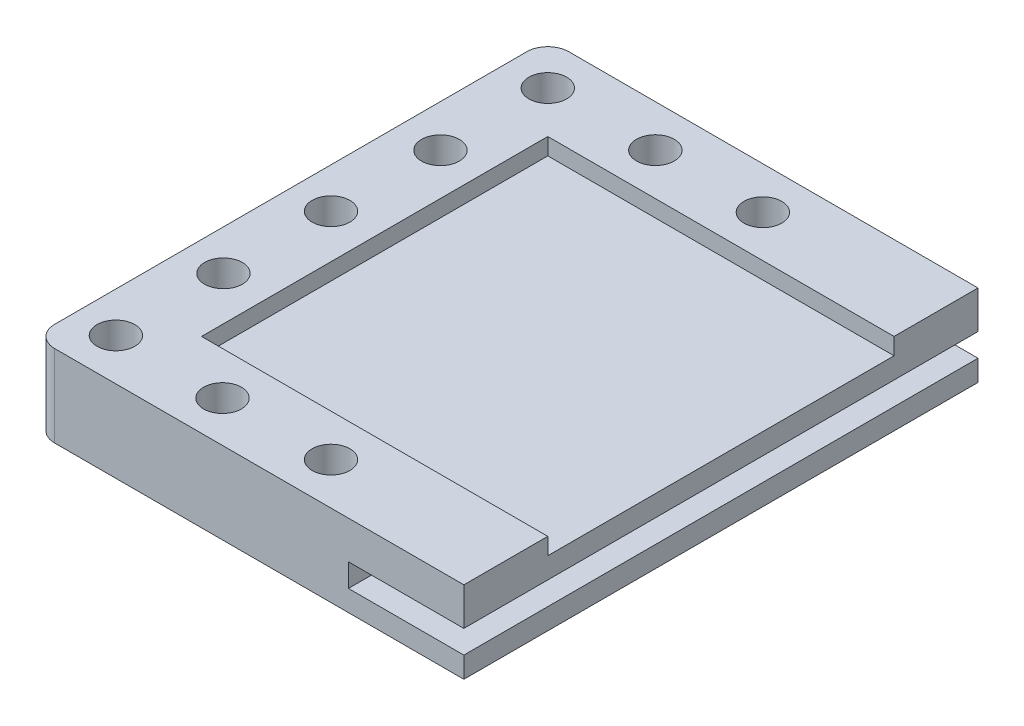
SolidWorks part; units mm, degrees
ref_plane "Front Plane" through (0, 0, 0) normal (0, 0, 1) x (1, 0, 0)
ref_plane "Top Plane" through (0, 0, 0) normal (0, 1, 0) x (1, 0, 0)
ref_plane "Right Plane" through (0, 0, 0) normal (1, 0, 0) x (0, 0, -1)
sketch "Sketch1" plane through (0, 0, 0) normal (0, 1, 0) x (1, 0, 0)
  line L1 (-14.684, 10.0891) -> (5.816, 10.0891)
  line L2 (-14.684, 10.0891) -> (-14.684, -14.4109)
  line L3 (-14.684, -14.4109) -> (5.816, -14.4109)
  line L4 (5.816, 10.0891) -> (5.816, -14.4109)
  dimension "D1" = 20.5
  dimension "D2" = 24.5
extrude "Boss-Extrude1" add sketch "Sketch1" along normal blind 3.1
sketch "Sketch2" plane through (0, 0, 14.4109) normal (0, 0, 1) x (1, 0, 0)
  line L0 (5.816, 3.1) -> (5.816, 0) construction
  line L1 (5.816, 2.1) -> (0.316, 2.1)
  line L2 (5.816, 2.1) -> (5.816, 1)
  line L3 (5.816, 1) -> (0.316, 1)
  line L4 (0.316, 2.1) -> (0.316, 1)
  line L5 (-14.684, 3.1) -> (5.816, 3.1) construction
  dimension "D1" = 5.5
  dimension "D2" = 1.1
  dimension "D3" = 1
extrude "Cut-Extrude1" cut sketch "Sketch2" against normal through all
sketch "Sketch3" plane through (0, 3.1, 0) normal (0, 1, 0) x (1, 0, 0)
  line L0 (-14.684, -14.4109) -> (5.816, -14.4109) construction
  line L1 (-14.684, 10.0891) -> (-10.684, 10.0891)
  line L2 (-14.684, 10.0891) -> (-14.684, -14.4109)
  line L3 (-14.684, -14.4109) -> (-10.684, -14.4109)
  line L4 (-10.684, 10.0891) -> (-10.684, -14.4109)
  line L5 (5.816, -14.4109) -> (5.816, 10.0891) construction
  line L6 (-10.684, 10.0891) -> (5.816, 10.0891)
  line L7 (-10.684, 10.0891) -> (-10.684, 6.0891)
  line L8 (-10.684, 6.0891) -> (5.816, 6.0891)
  line L9 (5.816, 10.0891) -> (5.816, 6.0891)
  line L11 (-10.684, -14.4109) -> (5.816, -14.4109)
  line L12 (-10.684, -14.4109) -> (-10.684, -10.4109)
  line L13 (-10.684, -10.4109) -> (5.816, -10.4109)
  line L14 (5.816, -14.4109) -> (5.816, -10.4109)
  line M7 (-14.684, 10.0891) -> (-14.684, -14.4109)
  line M8 (-14.684, -14.4109) -> (5.816, -14.4109)
  line M9 (5.816, -14.4109) -> (5.816, 10.0891)
  line M10 (5.816, 10.0891) -> (-14.684, 10.0891)
  dimension "D1" = 4
  dimension "D2" = 4
  dimension "D3" = 4
extrude "Boss-Extrude2" add sketch "Sketch3" along normal blind 0.8 contours L4 M10 M7 M8 | L4 L8 M9 M10 | L13 L4 M8 M9
sketch "Sketch4" plane through (0, 0, 0) normal (0, -1, 0) x (1, 0, 0)
  line L0 (5.816, 14.4109) -> (5.816, -10.0891) construction
  line L1 (5.816, -10.0891) -> (-14.684, -10.0891) construction
  circle A0 centre (3.066, -5.3391) radius 0.5501
  circle A5 centre (3.066, 4.6609) radius 0.5501
  circle A6 centre (3.066, -0.3391) radius 0.5501
  circle A7 centre (3.0468, 9.6608) radius 0.5501
  dimension "D1" = 2.75
  dimension "D2" = 5
  dimension "D3" = 5
  dimension "D4" = 5
  dimension "D5" = 4.75
  dimension "D6" = 0
  dimension "D7" = 0
hole_wizard "Tap Drill for M2.5x0.45 Tap1" positions "Sketch5" profile "Sketch6" hole size "M2.5x0.45" standard "ANSI Metric"
sketch "Sketch5" plane through (0, 0, 0) normal (0, -1, 0) x (-1, 0, 0)
  point P0 (-3.066, 5.3391)
  point P3 (-3.066, 0.3391)
  point P6 (-3.066, -4.6609)
  point P9 (-3.0468, -9.6608)
sketch "Sketch6" plane through (3.066, 0, -5.3391) normal (1, 0, 0) x (0, 0, -1)
  line L0 (0, 0) -> (0, 1.675)
  line L1 (0, 1.675) -> (1.125, 0.999)
  line L2 (1.125, 0.999) -> (1.125, 0)
  line L5 (1.125, 0) -> (0, 0)
  line L10 (0, 1.675) -> (-1.125, 0.999) construction
  line L11 (0, -6.35) -> (0, 107.95) construction
  dimension "Hole Dia." = 2.25
  dimension "Hole Depth" = 0.999
  dimension "Drill Angle" = 118
sketch "Sketch7" plane through (0, 3.9, 0) normal (0, 1, 0) x (1, 0, 0)
  line L0 (-14.684, 10.0891) -> (-14.684, -14.4109) construction
  line L2 (5.816, 10.0891) -> (-14.684, 10.0891) construction
  circle A0 centre (-12.684, 8.0891) radius 0.882
  circle A1 centre (-12.7647, -12.4109) radius 0.882
  circle A2 centre (-12.6745, 2.9641) radius 0.882
  circle A3 centre (-12.7647, -2.1609) radius 0.882
  circle A4 centre (-12.7647, -7.2859) radius 0.882
  circle A5 centre (-7.559, 8.0891) radius 0.882
  circle A6 centre (-2.434, 8.0891) radius 0.882
  circle A7 centre (-2.5147, -12.4109) radius 0.882
  circle A9 centre (-7.6397, -12.4567) radius 0.882
  dimension "D1" = 2
  dimension "D2" = 2
  dimension "D3" = 5.125
  dimension "D4" = 5.125
  dimension "D5" = 5.125
  dimension "D6" = 5.125
  dimension "D7" = 5.125
  dimension "D8" = 5.125
  dimension "D10" = 5.125
  dimension "D11" = 5.125
hole_wizard "Tap Drill for M2x0.4 Tap2" positions "Sketch8" profile "Sketch10" hole size "M2x0.4" standard "ANSI Metric" end condition through all
sketch "Sketch8" plane through (0, 3.9, 0) normal (0, 1, 0) x (1, 0, 0)
  point P0 (-12.684, 8.0891)
  point P4 (-12.6745, 2.9641)
  point P7 (-12.7647, -2.1609)
  point P10 (-12.7647, -7.2859)
  point P13 (-12.7647, -12.4109)
  point P16 (-7.559, 8.0891)
  point P19 (-2.434, 8.0891)
  point P28 (-2.5147, -12.4109)
  point P31 (-7.6397, -12.4567)
sketch "Sketch10" plane through (-12.684, 3.9, -8.0891) normal (1, 0, 0) x (0, 0, 1)
  line L0 (0, 0) -> (0, 3.9)
  line L1 (0, 3.9) -> (0.9, 3.9)
  line L2 (0.9, 3.9) -> (0.9, 0)
  line L5 (0.9, 0) -> (0, 0)
  line L11 (0, -6.35) -> (0, 107.95) construction
  dimension "Thru Hole Dia." = 1.8
  dimension "Thru Hole Depth" = 3.9
fillet "Fillet2" radius 1 2 edges at (-14.684, 1.95, 14.4109) (-14.684, 1.95, -10.0891)
equation "\"samplewidth\" = 16 + \"dimtolerance\""
equation "\"D1@Sketch1\"=\"samplewidth\" + 4"
equation "\"sampleheight\"= 16 + \"dimtolerance\""
equation "\"D2@Sketch1\"=\"sampleheight\" + 8"
equation "\"stickthickness\"=1.1"
equation "\"D1@Boss-Extrude1\"=\"stickthickness\"+2"
equation "\"stickwidth\"= 5.5"
equation "\"D1@Sketch2\"=\"stickwidth\""
equation "\"D2@Sketch2\"=\"stickthickness\""
equation "\"samplethickness\"=0.8"
equation "\"D1@Boss-Extrude2\"=\"samplethickness\""
equation "\"D1@Sketch4\"=\"stickwidth\"/2"
equation "\"dimtolerance\"= 0.5"
equation "\"D3@Sketch7\"=(\"sampleheight\" +4)/4"
equation "\"D4@Sketch7\"=(\"sampleheight\" +4)/4"
equation "\"D5@Sketch7\"=(\"sampleheight\" +4)/4"
equation "\"D6@Sketch7\"=(\"sampleheight\" +4)/4"
equation "\"D7@Sketch7\"=(\"samplewidth\" +4)/4"
equation "\"D8@Sketch7\"=(\"samplewidth\" +4)/4"
equation "\"D10@Sketch7\"=(\"samplewidth\" +4)/4"
equation "\"D11@Sketch7\"=(\"samplewidth\" +4)/4"
